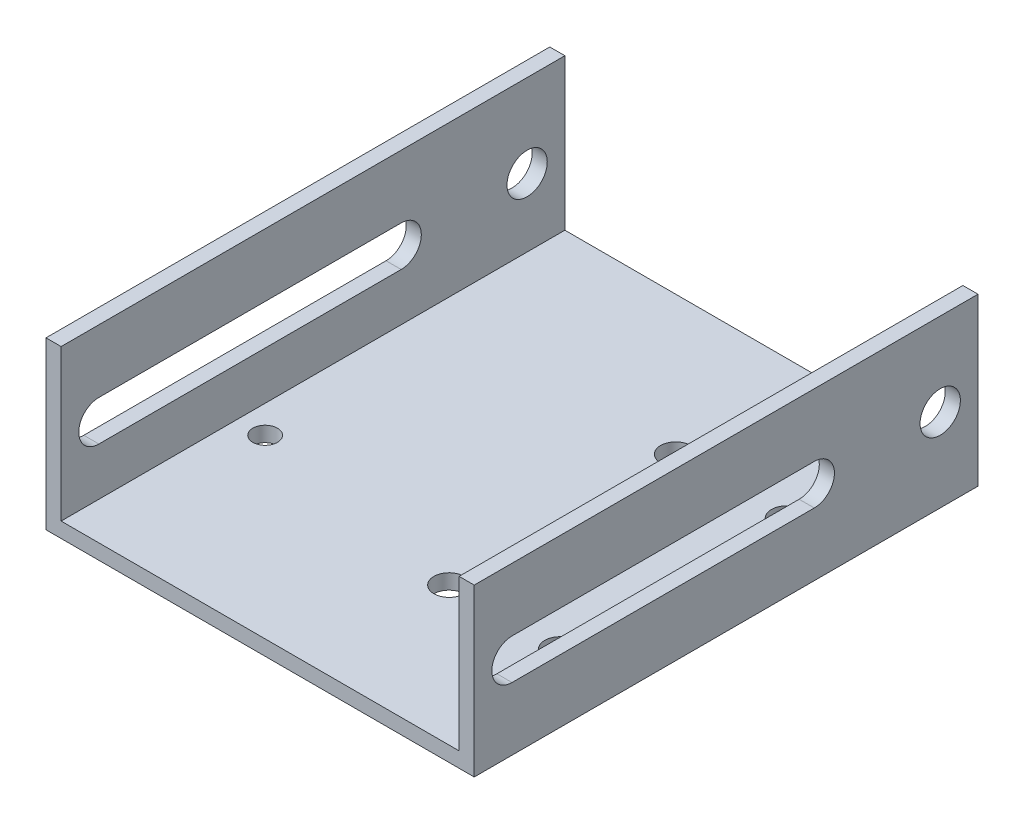
SolidWorks part; units mm, degrees
ref_plane "前视基准面" through (0, 0, 0) normal (0, 0, 1) x (1, 0, 0)
ref_plane "上视基准面" through (0, 0, 0) normal (0, 1, 0) x (1, 0, 0)
ref_plane "右视基准面" through (0, 0, 0) normal (1, 0, 0) x (0, 0, -1)
sketch "草图1" plane through (0, 0, 0) normal (0, 1, 0) x (1, 0, 0)
  line L1 (-42.5, -50) -> (42.5, -50)
  line L2 (-42.5, -50) -> (-42.5, 50)
  line L3 (-42.5, 50) -> (42.5, 50)
  line L4 (42.5, -50) -> (42.5, 50)
  line L5 (-42.5, -50) -> (42.5, 50) construction
  line L6 (-42.5, 50) -> (42.5, -50) construction
  point P0 (0, 0)
  dimension "D1" = 100
  dimension "D2" = 85
extrude "凸台-拉伸1" add sketch "草图1" along normal blind 3
sketch "草图2" plane through (0, 3, 0) normal (0, 1, 0) x (1, 0, 0)
  line L0 (-42.5, -50) -> (42.5, -50) construction
  line L1 (-42.5, 50) -> (-39.5, 50)
  line L2 (-42.5, 50) -> (-42.5, -50)
  line L3 (-42.5, -50) -> (-39.5, -50)
  line L4 (-39.5, 50) -> (-39.5, -50)
  line L5 (42.5, 50) -> (-42.5, 50) construction
  line L6 (42.5, -50) -> (39.5, -50)
  line L7 (42.5, -50) -> (42.5, 50)
  line L8 (42.5, 50) -> (39.5, 50)
  line L9 (39.5, -50) -> (39.5, 50)
  dimension "D1" = 3
  dimension "D2" = 3
extrude "凸台-拉伸2" add sketch "草图2" along normal blind 30
sketch "草图3" plane through (42.5, 0, 0) normal (1, 0, 0) x (0, 0, -1)
  line L0 (-50, 16.5) -> (50, 16.5) construction
  line L1 (-50, 33) -> (-50, 0) construction
  line L2 (50, 33) -> (50, 0) construction
  line L4 (-42.5, 12.5) -> (17.5, 12.5)
  line L5 (-42.5, 12.5) -> (-42.5, 20.5) construction
  line L6 (-42.5, 20.5) -> (17.5, 20.5)
  line L7 (17.5, 12.5) -> (17.5, 20.5) construction
  line L8 (-42.5, 12.5) -> (17.5, 20.5) construction
  line L9 (-42.5, 20.5) -> (17.5, 12.5) construction
  circle A0 centre (42.5, 16.5) radius 4
  arc A1 (17.5, 12.5) -> (17.5, 20.5) centre (17.5, 16.5) ccw
  arc A2 (-42.5, 20.5) -> (-42.5, 12.5) centre (-42.5, 16.5) ccw
  point P8 (-12.5, 16.5)
  dimension "D1" = 8
  dimension "D2" = 4
  dimension "D3" = 60
  dimension "D4" = 85
  dimension "D5" = 7.5
extrude "切除-拉伸1" cut sketch "草图3" against normal up to surface (85 mm away) up to face at (-42.5, 16.5, 0)
sketch "草图4" plane through (0, 0, 0) normal (0, -1, 0) x (1, 0, 0)
  line L0 (10, 0) -> (32, 0) construction
  line L1 (32, 22.5) -> (10, 22.5) construction
  line L2 (32, 22.5) -> (32, -22.5) construction
  line L3 (32, -22.5) -> (10, -22.5) construction
  line L4 (10, 22.5) -> (10, -22.5) construction
  line L5 (32, 22.5) -> (10, -22.5) construction
  line L6 (32, -22.5) -> (10, 22.5) construction
  line L7 (21, -22.5) -> (21, 22.5) construction
  line L8 (42.5, -50) -> (-42.5, -50) construction
  line L9 (0, -50) -> (0, 50) construction
  line L10 (-42.5, 50) -> (42.5, 50) construction
  circle A0 centre (21, 0) radius 3
  circle A1 centre (10, -22.5) radius 3
  circle A2 centre (32, -22.5) radius 3
  circle A3 centre (10, 22.5) radius 3
  circle A4 centre (32, 22.5) radius 3
  circle A5 centre (21, -45) radius 2
  circle A6 centre (-34, 15) radius 2.4454
  point P0 (21, 0)
  dimension "D1" = 45
  dimension "D2" = 22
  dimension "D3" = 45
  dimension "D4" = 4
  dimension "D5" = 6
  dimension "D6" = 6
  dimension "D7" = 5
  dimension "D8" = 21
  dimension "D9" = 60
  dimension "D10" = 55
extrude "切除-拉伸3" cut sketch "草图4" against normal through all
